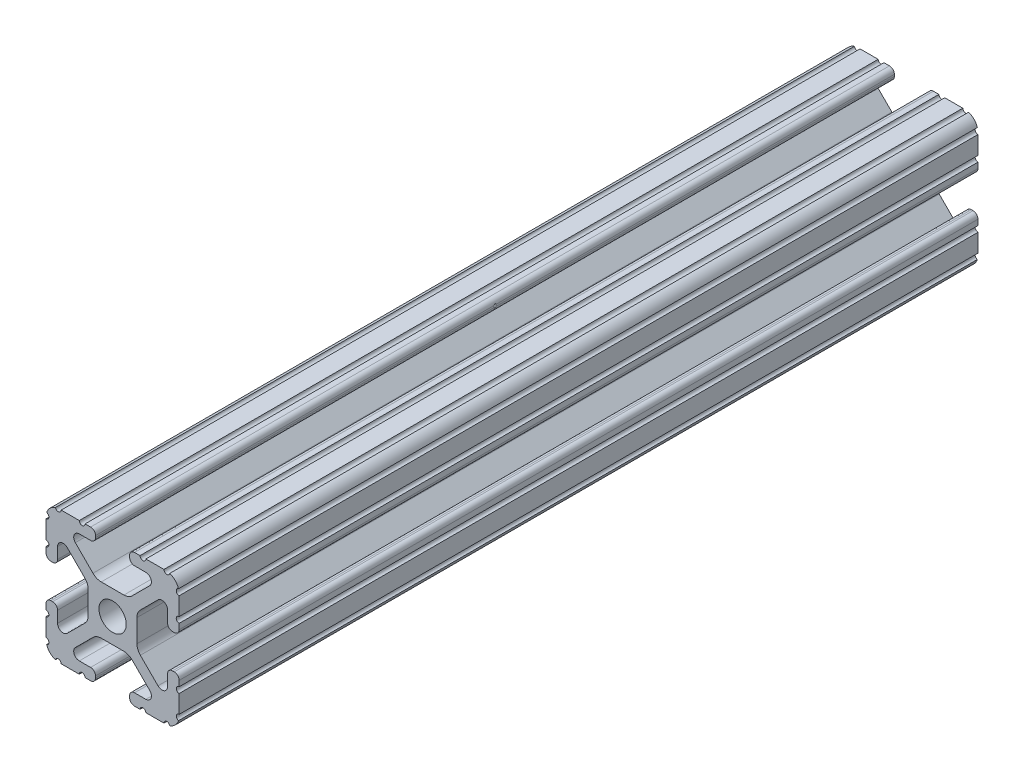
SolidWorks part; units mm, degrees
ref_plane "Front Plane" through (0, 0, 0) normal (0, 0, 1) x (1, 0, 0)
ref_plane "Top Plane" through (0, 0, 0) normal (0, 1, 0) x (1, 0, 0)
ref_plane "Right Plane" through (0, 0, 0) normal (1, 0, 0) x (0, 0, -1)
sketch "Sketch2" plane through (0, 0, 0) normal (0, 0, 1) x (1, 0, 0)
  line L0 (0, 12.7) -> (0, -12.7) construction
  line L1 (-12.7, 0) -> (12.7, 0) construction
  line L2 (3.2512, -12.7) -> (12.7, -12.7)
  line L3 (12.7, -12.7) -> (12.7, -3.2512)
  line L4 (3.2512, -12.7) -> (3.2512, -10.4902)
  line L5 (3.2512, -10.4902) -> (8.9276, -10.4902)
  line L6 (8.9276, -10.4902) -> (3.0856, -4.6482)
  line L7 (0, 0) -> (12.7, -12.7) construction
  line L8 (12.7, -3.2512) -> (10.4902, -3.2512)
  line L9 (10.4902, -3.2512) -> (10.4902, -8.9276)
  line L10 (10.4902, -8.9276) -> (4.6482, -3.0856)
  circle A0 centre (0, 0) radius 2.6035
  arc A1 (6.3485, -10.4902) -> (7.1039, -8.6665) centre (6.3485, -9.4219) ccw construction
  point P8 (0, -4.6482)
  dimension "Center Hole Diameter" = 5.207
  dimension "Rail Height" = 25.4
  dimension "Rail Width" = 25.4
  dimension "T-Slot Width" = 6.5024
  dimension "Slot Inner Width" = 14.8336
  dimension "Thickness" = 2.2098
  dimension "Slot Depth" = 5.842
  dimension "D1" = 2.2098
sketch "Sketch3" plane through (0, 0, 0) normal (1, 0, 0) x (0, 0, -1)
  line L0 (-76.2, -12.7) -> (76.2, -12.7) construction
  line L1 (-68.58, 0) -> (68.58, 0) construction
  dimension "Length" = 152.4
  dimension "D1" = 137.16
sketch "Sketch4" plane through (0, 0, 0) normal (0, 0, 1) x (1, 0, 0)
  line L0 (4.1904, -12.7) -> (10.1173, -12.7)
  line L1 (3.2512, -12.7) -> (12.7, -12.7) construction
  line L2 (3.2512, -12.7) -> (3.2512, -10.4902) construction
  line L3 (3.2512, -10.4902) -> (8.9276, -10.4902) construction
  line L4 (3.2512, -11.4294) -> (3.2512, -11.7608)
  line L5 (4.1904, -10.4902) -> (6.3485, -10.4902)
  line L6 (0, -4.6482) -> (2.164, -4.6482)
  line L7 (8.9276, -10.4902) -> (3.0856, -4.6482) construction
  line L8 (3.7373, -5.2999) -> (7.1039, -8.6665)
  line L9 (12.7, -12.7) -> (12.7, -3.2512) construction
  line L10 (10.4902, -8.9276) -> (4.6482, -3.0856) construction
  line L11 (10.4902, -3.2512) -> (10.4902, -8.9276) construction
  line L12 (10.4902, -6.3485) -> (10.4902, -4.1904)
  line L13 (12.7, -3.2512) -> (10.4902, -3.2512) construction
  line L14 (11.4294, -3.2512) -> (11.7608, -3.2512)
  line L15 (12.7, -4.1904) -> (12.7, -10.1173)
  line L16 (8.6665, -7.1039) -> (5.2999, -3.7373)
  line L17 (4.6482, 0) -> (4.6482, -2.164)
  line L18 (-12.7, 0) -> (12.7, 0) construction
  line L19 (0, -4.6482) -> (0, -2.6035)
  line L20 (0, 12.7) -> (0, -12.7) construction
  line L21 (4.6482, 0) -> (2.6035, 0)
  arc A0 (3.2512, -11.7608) -> (4.1904, -12.7) centre (4.1904, -11.7608) ccw
  arc A2 (3.2512, -11.4294) -> (4.1904, -10.4902) centre (4.1904, -11.4294) cw
  arc A3 (6.3485, -10.4902) -> (7.1039, -8.6665) centre (6.3485, -9.4219) ccw
  arc A4 (2.164, -4.6482) -> (3.7373, -5.2999) centre (2.164, -6.8732) cw
  arc A5 (10.1173, -12.7) -> (12.7, -10.1173) centre (10.1173, -10.1173) ccw
  arc A6 (8.6665, -7.1039) -> (10.4902, -6.3485) centre (9.4219, -6.3485) ccw
  arc A7 (10.4902, -4.1904) -> (11.4294, -3.2512) centre (11.4294, -4.1904) cw
  arc A8 (11.7608, -3.2512) -> (12.7, -4.1904) centre (11.7608, -4.1904) cw
  arc A9 (5.2999, -3.7373) -> (4.6482, -2.164) centre (6.8732, -2.164) cw
  circle A10 centre (0, 0) radius 2.6035 construction
  arc A11 (0, -2.6035) -> (2.6035, 0) centre (0, 0) ccw
  dimension "D1" = 2.5827
  dimension "D2" = 2.225
  dimension "D3" = 0.9392
extrude "Boss-Extrude1" add sketch "Sketch4" along normal mid plane 152.4
sketch "Sketch5" plane through (0, 0, 0) normal (0, 0, 1) x (1, 0, 0)
  line L0 (3.2512, -12.7) -> (12.7, -12.7) construction
  line L1 (4.1904, -10.4902) -> (6.3485, -10.4902) construction
  line L3 (0, 0) -> (12.7, -12.7) construction
  line L4 (6.3485, -10.4902) -> (6.3485, -12.7) construction
  line L5 (8.9276, -10.4902) -> (3.0856, -4.6482) construction
  circle A0 centre (10.3562, -12.7) radius 0.5524
  circle A1 centre (5.796, -12.7) radius 0.5524
  circle A2 centre (12.7, -10.3562) radius 0.5524
  circle A3 centre (12.7, -5.796) radius 0.5524
  point P10 (5.2694, -10.4902)
  point P12 (9.4219, -6.3485)
  dimension "D1" = 1.1049
extrude "Cut-Extrude1" cut sketch "Sketch5" against normal through all both and the other way through all
mirror "Mirror1" about plane through (0, 0, 0) normal (1, 0, 0) of bodies 137 134
mirror "Mirror2" about plane through (0, 0, 0) normal (0, 1, 0) of bodies 135
sketch "Sketch6" plane through (0, 12.7, 0) normal (0, 1, 0) x (1, 0, 0)
  line L0 (0, 76.2) -> (0, -76.2) construction
  line L1 (-2.164, 76.2) -> (2.164, 76.2) construction
  line L2 (-2.164, -76.2) -> (2.164, -76.2) construction
  circle A0 centre (0, 0) radius 3.2639
  dimension "D1" = 6.5278
extrude "Cut-Extrude2" cut sketch "Sketch6" against normal through all
sketch "Sketch7" plane through (0, 12.7, 0) normal (0, 1, 0) x (1, 0, 0)
  line L0 (0, 76.2) -> (0, -76.2) construction
  line L1 (-2.164, 76.2) -> (2.164, 76.2) construction
  line L2 (-2.164, -76.2) -> (2.164, -76.2) construction
  line L3 (0, 0) -> (23.0584, 0) construction
  circle A0 centre (0, 19.05) radius 3.2639
  circle A1 centre (0, -19.05) radius 3.2639
  dimension "D1" = 6.5278
  dimension "D2" = 38.1
equation "\"D1@Boss-Extrude1\"=\"Length@Sketch3\""
equation "\"D1@Sketch2\"=\"Thickness@Sketch2\""
equation "\"D2@Sketch4\"=\"Slot Inner Width@Sketch2\"*0.15"
equation "\"D1@Sketch4\"=\"D3@Sketch4\"*2.75"
equation "\"D3@Sketch4\"=\"Thickness@Sketch2\"*0.425"
equation "\"D1@Sketch5\"=\"Thickness@Sketch2\"*0.5"
equation "\"D1@Sketch3\"=\"Length@Sketch3\"*0.9"
